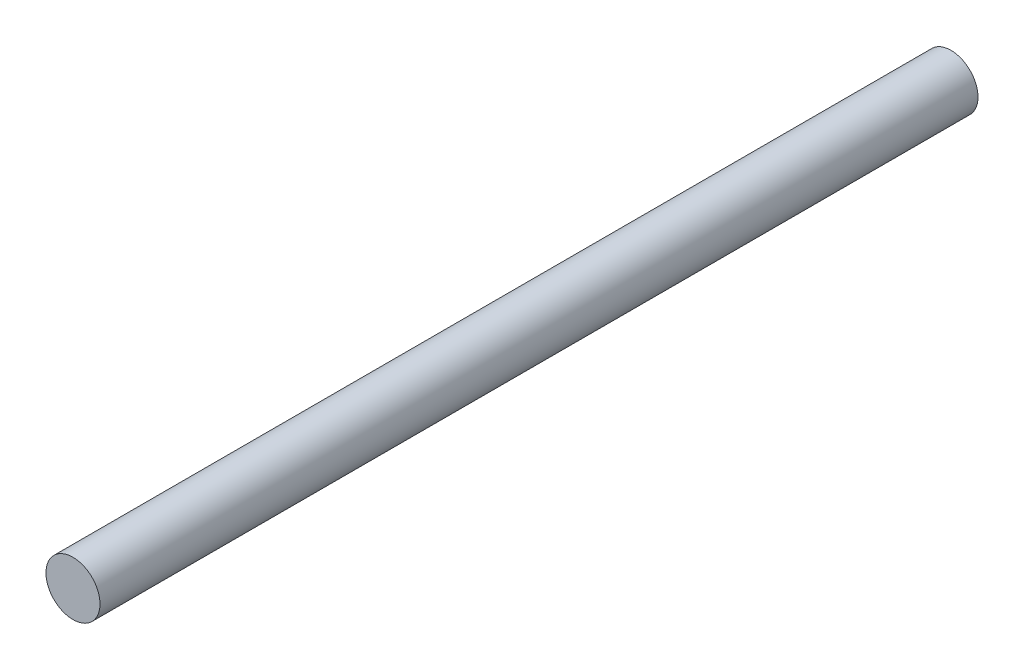
SolidWorks part; units mm, degrees
ref_plane "前视基准面" through (0, 0, 0) normal (0, 0, 1) x (1, 0, 0)
ref_plane "上视基准面" through (0, 0, 0) normal (0, 1, 0) x (1, 0, 0)
ref_plane "右视基准面" through (0, 0, 0) normal (1, 0, 0) x (0, 0, -1)
sketch "草图1" plane through (0, 0, 0) normal (0, 0, 1) x (1, 0, 0)
  circle A0 centre (0, 0) radius 4
  dimension "D1" = 8
extrude "凸台-拉伸1" add sketch "草图1" along normal blind 130
